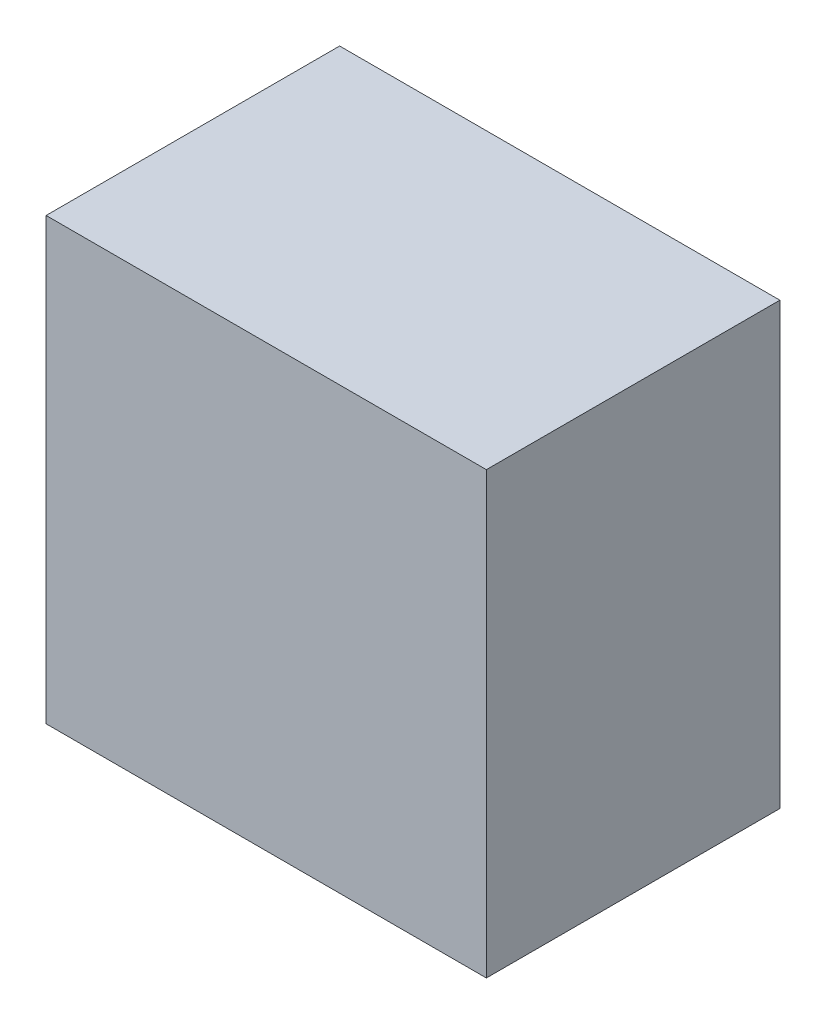
SolidWorks part; units mm, degrees
ref_plane "Front Plane" through (0, 0, 0) normal (0, 0, 1) x (1, 0, 0)
ref_plane "Top Plane" through (0, 0, 0) normal (0, 1, 0) x (1, 0, 0)
ref_plane "Right Plane" through (0, 0, 0) normal (1, 0, 0) x (0, 0, -1)
sketch "Sketch1" plane through (0, 0, 0) normal (0, 0, 1) x (1, 0, 0)
  line L1 (0, 0) -> (300, 0)
  line L2 (0, 0) -> (0, -300)
  line L3 (0, -300) -> (300, -300)
  line L4 (300, 0) -> (300, -300)
  dimension "D1" = 300
  dimension "D2" = 300
extrude "Boss-Extrude1" add sketch "Sketch1" along normal blind 200
